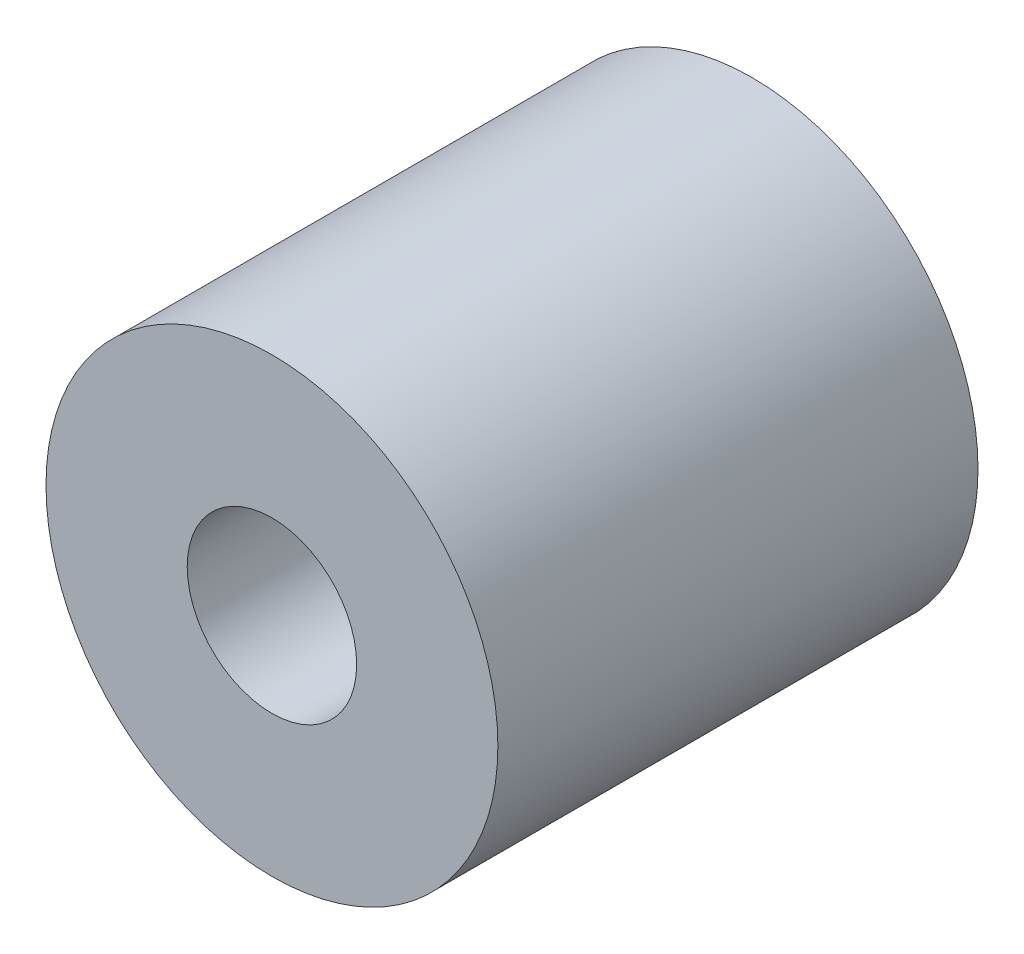
SolidWorks part; units mm, degrees
ref_plane "Front Plane" through (0, 0, 0) normal (0, 0, 1) x (1, 0, 0)
ref_plane "Top Plane" through (0, 0, 0) normal (0, 1, 0) x (1, 0, 0)
ref_plane "Right Plane" through (0, 0, 0) normal (1, 0, 0) x (0, 0, -1)
sketch "Sketch1" plane through (0, 0, 0) normal (0, 0, 1) x (1, 0, 0)
  circle A0 centre (0, 0) radius 4
  circle A1 centre (0, 0) radius 3
  dimension "D1" = 8
  dimension "D2" = 6
extrude "Boss-Extrude1" add sketch "Sketch1" along normal blind 8.5
sketch "Sketch2" plane through (0, 0, 8.5) normal (0, 0, 1) x (1, 0, 0)
  circle A0 centre (0, 0) radius 3
  circle A1 centre (0, 0) radius 1.5
  dimension "D1" = 3
extrude "Boss-Extrude2" add sketch "Sketch2" against normal offset from surface (6 mm away) 2.5 up to face at (4, 0, 0)
